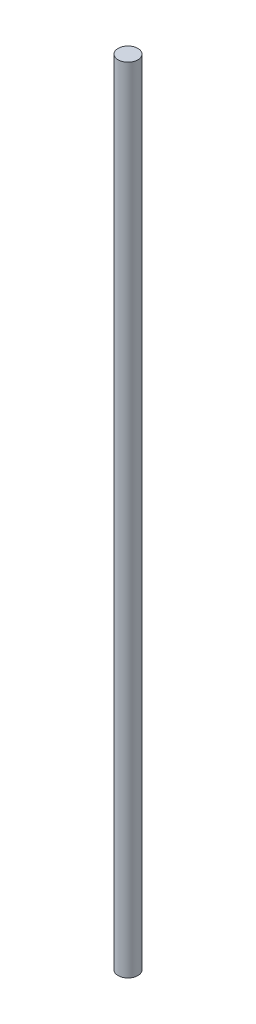
SolidWorks part; units mm, degrees
ref_plane "Front Plane" through (0, 0, 0) normal (0, 0, 1) x (1, 0, 0)
ref_plane "Top Plane" through (0, 0, 0) normal (0, 1, 0) x (1, 0, 0)
ref_plane "Right Plane" through (0, 0, 0) normal (1, 0, 0) x (0, 0, -1)
sketch "Sketch1" plane through (0, 0, 0) normal (0, 1, 0) x (1, 0, 0)
  circle A0 centre (0, 0) radius 2.5
extrude "Boss-Extrude1" add sketch "Sketch1" along normal blind 200
